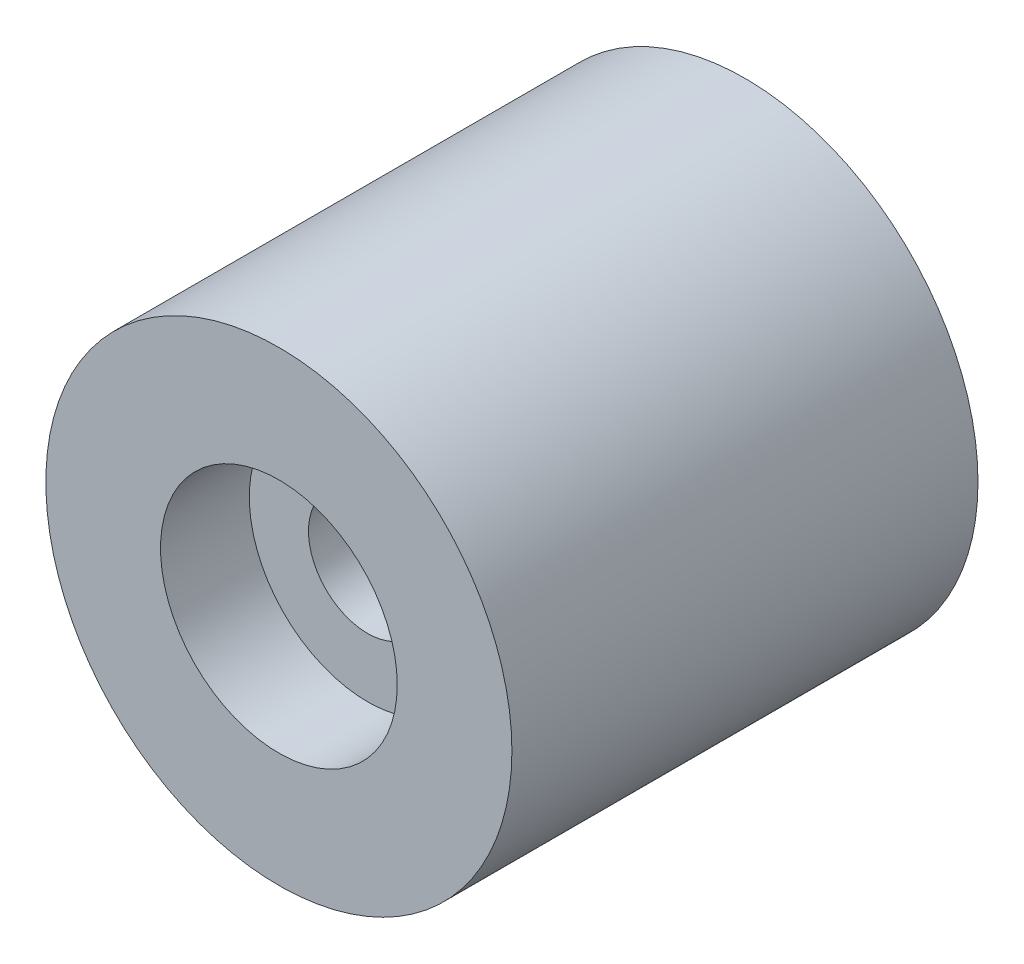
SolidWorks part; units mm, degrees
ref_plane "Front Plane" through (0, 0, 0) normal (1, 0, 0) x (0, 1, 0)
ref_plane "Top Plane" through (0, 0, 0) normal (0, 0, 1) x (0, 1, 0)
ref_plane "Right Plane" through (0, 0, 0) normal (0, 1, 0) x (-1, 0, 0)
sketch "Sketch1" plane through (0, 0, 0) normal (0, 0, 1) x (0, 1, 0)
  circle A0 centre (0, 0) radius 7.875
  circle A1 centre (0, 0) radius 2
  dimension "D1" = 15.75
  dimension "D2" = 4
extrude "Boss-Extrude1" add sketch "Sketch1" along normal blind 15.75
sketch "Sketch2" plane through (0, 0, 15.75) normal (0, 0, 1) x (1, 0, 0)
  circle A0 centre (0, 0) radius 4
  dimension "D1" = 8
extrude "Cut-Extrude1" cut sketch "Sketch2" against normal blind 3
